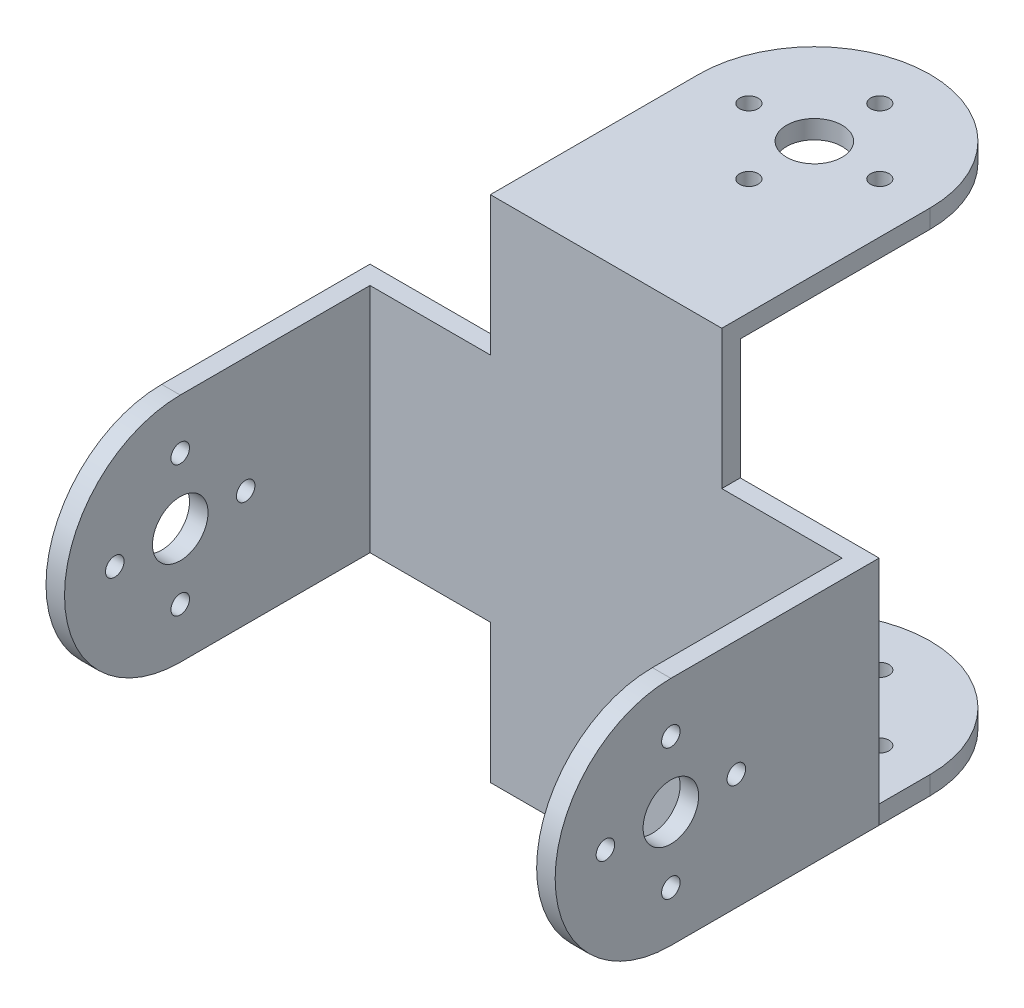
SolidWorks part; units mm, degrees
ref_plane "前视基准面" through (0, 0, 0) normal (0, 0, 1) x (1, 0, 0)
ref_plane "上视基准面" through (0, 0, 0) normal (0, 1, 0) x (1, 0, 0)
ref_plane "右视基准面" through (0, 0, 0) normal (1, 0, 0) x (0, 0, -1)
sketch "草图1" plane through (0, 0, 0) normal (0, 0, 1) x (1, 0, 0)
  line L0 (0, 0) -> (50000, 0) construction
  line L1 (0, 0) -> (0, 50000) construction
  line L2 (-27.5, 12.5) -> (27.5, 12.5)
  line L3 (-27.5, 27.5) -> (27.5, 27.5)
  line L4 (-27.5, 27.5) -> (-27.5, -27.5)
  line L5 (-27.5, -27.5) -> (27.5, -27.5)
  line L6 (27.5, 27.5) -> (27.5, -27.5)
  line L7 (-27.5, -12.5) -> (27.5, -12.5)
  line L8 (-12.5, -12.5) -> (-12.5, -27.5)
  line L9 (12.5, -12.5) -> (12.5, -27.5)
  line L10 (12.5, 12.5) -> (12.5, 27.5)
  line L11 (-12.5, 12.5) -> (-12.5, 27.5)
  dimension "D1" = 55
  dimension "D2" = 55
  dimension "D3" = 12.5
  dimension "D4" = 25
extrude "凸台-拉伸2" add sketch "草图1" along normal blind 2 contours L4 L7 L6 L2 | L11 L2 L10 L3 | L9 L7 L8 L5
sketch "草图3" plane through (0, 0, 2) normal (0, 0, 1) x (1, 0, 0)
  line L0 (0, 0) -> (50000, 0) construction
  line L1 (0, 0) -> (0, 50000) construction
  line L2 (-25.5, 12.5) -> (-25.5, -12.5)
  line L3 (-27.5, 12.5) -> (-12.5, 12.5) construction
  line L4 (-27.5, -12.5) -> (-12.5, -12.5) construction
  line L5 (-27.5, 12.5) -> (-27.5, -12.5) construction
  line L6 (25.5, 12.5) -> (25.5, -12.5)
  line L7 (25.5, 12.5) -> (27.5, 12.5)
  line L8 (27.5, 12.5) -> (27.5, -12.5)
  line L9 (27.5, -12.5) -> (25.5, -12.5)
  line L10 (-25.5, -12.5) -> (-27.5, -12.5)
  line L11 (-27.5, -12.5) -> (-27.5, 12.5)
  line L12 (-27.5, 12.5) -> (-25.5, 12.5)
  line M15 (12.5, -12.5) -> (27.5, -12.5)
  line M16 (27.5, -12.5) -> (27.5, 12.5)
  line M17 (27.5, 12.5) -> (12.5, 12.5)
  dimension "D1" = 2
extrude "凸台-拉伸3" add sketch "草图3" along normal blind 33 contours L6 M17 M15 M16 | L12 L2 L10 L11
sketch "草图4" plane through (0, 0, 0) normal (0, 0, -1) x (-1, 0, 0)
  line L0 (-12.5, 25.5) -> (12.5, 25.5)
  line L1 (-12.5, 12.5) -> (-12.5, 27.5) construction
  line L2 (12.5, 12.5) -> (12.5, 27.5) construction
  line L3 (-12.5, -25.5) -> (12.5, -25.5)
  line L4 (-12.5, -12.5) -> (-12.5, -27.5) construction
  line L5 (12.5, -12.5) -> (12.5, -27.5) construction
  line L6 (12.5, 27.5) -> (-12.5, 27.5) construction
  line L7 (12.5, -27.5) -> (-12.5, -27.5) construction
  line L8 (12.5, 25.5) -> (12.5, 27.5)
  line L9 (12.5, 27.5) -> (-12.5, 27.5)
  line L10 (-12.5, 27.5) -> (-12.5, 25.5)
  line L11 (-12.5, -25.5) -> (-12.5, -27.5)
  line L12 (-12.5, -27.5) -> (12.5, -27.5)
  line L13 (12.5, -27.5) -> (12.5, -25.5)
  dimension "D1" = 2
  dimension "D2" = 2
extrude "凸台-拉伸4" add sketch "草图4" along normal blind 33
sketch "草图5" plane through (-27.5, 0, 0) normal (-1, 0, 0) x (0, 0, 1)
  line L0 (0, 0) -> (50000, 0) construction
  line L1 (35, -12.5) -> (35, 12.5) construction
  line L2 (22.5, 12.5) -> (35, 12.5)
  line L3 (35, 12.5) -> (35, -12.5)
  line L4 (35, -12.5) -> (22.5, -12.5)
  line L5 (22.5, 0) -> (22.5, 50000) construction
  circle A0 centre (22.5, 0) radius 12.5
  circle A1 centre (29.6825, 0) radius 1
  circle A2 centre (15.3175, 0) radius 1
  circle A3 centre (22.5, 6.9578) radius 1
  circle A4 centre (22.5, -6.9578) radius 1
  line M3 (0, -12.5) -> (35, -12.5)
  line M4 (35, -12.5) -> (35, 12.5)
  line M5 (35, 12.5) -> (0, 12.5)
  dimension "D1" = 12.5
  dimension "D2" = 10
extrude "切除-拉伸2" cut sketch "草图5" against normal through all contours A0 L3 M5 | A0 M3 M4 | A1 | A3 | A2 | A4
sketch "草图6" plane through (0, 27.5, 0) normal (0, 1, 0) x (1, 0, 0)
  line L0 (0, 0) -> (0, 50000) construction
  line L1 (-12.5, 33) -> (12.5, 33) construction
  line L2 (-12.5, 20.5) -> (-12.5, 33)
  line L3 (-12.5, 33) -> (12.5, 33)
  line L4 (12.5, 33) -> (12.5, 20.5)
  line L5 (0.3699, 20.5) -> (50000.3699, 20.5) construction
  circle A0 centre (0, 20.5) radius 12.5
  circle A1 centre (0, 28.1221) radius 1
  circle A2 centre (0, 12.8779) radius 1
  circle A3 centre (-6.4732, 20.5) radius 1
  circle A4 centre (6.4732, 20.5) radius 1
  line M6 (12.5, -2) -> (12.5, 33)
  line M7 (12.5, 33) -> (-12.5, 33)
  line M8 (-12.5, 33) -> (-12.5, -2)
  dimension "D1" = 12.5
  dimension "D2" = 10
extrude "切除-拉伸3" cut sketch "草图6" against normal through all contours A0 L3 M8 | A0 M6 M7 | A4 | A1 | A3 | A2
sketch "草图7" plane through (0, 27.5, 0) normal (0, 1, 0) x (1, 0, 0)
  line L0 (-6.4732, 20.5) -> (49993.5268, 20.5) construction
  line L1 (0, 12.8779) -> (0, 50012.8779) construction
  circle A0 centre (0, 20.5) radius 3
extrude "切除-拉伸4" cut sketch "草图7" against normal through all contours A0
sketch "草图8" plane through (27.5, 0, 0) normal (1, 0, 0) x (0, 0, -1)
  line L0 (-15.3175, 0) -> (49984.6825, 0) construction
  line L1 (-22.5, -6.9578) -> (-22.5, 49993.0422) construction
  circle A0 centre (-22.5, 0) radius 3
extrude "切除-拉伸5" cut sketch "草图8" against normal through all
sketch "草图9" plane through (27.5, 0, 0) normal (1, 0, 0) x (0, 0, -1)
  circle A0 centre (-22.5, 0) radius 3
  circle A1 centre (-22.5, 0) radius 12.5
extrude "凸台-拉伸5" add sketch "草图9" against normal blind 2
sketch "草图10" plane through (-27.5, 0, 0) normal (-1, 0, 0) x (0, 0, 1)
  circle A0 centre (22.5, 0) radius 12.5
  circle A1 centre (22.5, 0) radius 3
extrude "凸台-拉伸6" add sketch "草图10" against normal blind 2
sketch "草图11" plane through (-27.5, 0, 0) normal (-1, 0, 0) x (0, 0, 1)
  line L0 (22.5, 0) -> (22.5, 50000) construction
  line L1 (22.5, 0) -> (50022.5, 0) construction
  line L2 (22.5, 7.0711) -> (22.5, 0)
  line L3 (22.5, 0) -> (29.5711, 0)
  line L4 (22.5, 0) -> (-35332.8391, 35355.3391) construction
  circle A1 centre (22.5, 7.0711) radius 1
  circle A2 centre (29.5711, 0) radius 1
  circle A3 centre (22.5, -7.0711) radius 1
  circle A4 centre (15.4289, 0) radius 1
  dimension "D1" = 10
extrude "切除-拉伸6" cut sketch "草图11" against normal through all contours A4 | A1 | A2 | A3
sketch "草图12" plane through (0, 27.5, 0) normal (0, 1, 0) x (1, 0, 0)
  circle A0 centre (0, 20.5) radius 12.5
  circle A1 centre (0, 20.5) radius 3
extrude "凸台-拉伸7" add sketch "草图12" against normal blind 2
sketch "草图13" plane through (0, -27.5, 0) normal (0, -1, 0) x (1, 0, 0)
  circle A0 centre (0, -20.5) radius 3
  circle A1 centre (0, -20.5) radius 12.5
extrude "凸台-拉伸8" add sketch "草图13" against normal blind 2
sketch "草图14" plane through (0, -27.5, 0) normal (0, -1, 0) x (-1, 0, 0)
  line L0 (0, 20.5) -> (-50000, 20.5) construction
  line L1 (0, 20.5) -> (0, -49979.5) construction
  line L2 (0, 13.4289) -> (0, 20.5)
  line L3 (0, 20.5) -> (-7.0711, 20.5)
  line L4 (0, 20.5) -> (35355.3391, -35334.8391) construction
  circle A2 centre (0, 13.4289) radius 1
  circle A3 centre (-7.0711, 20.5) radius 1
  circle A4 centre (0, 27.5711) radius 1
  circle A5 centre (7.0711, 20.5) radius 1
  dimension "D1" = 10
extrude "切除-拉伸7" cut sketch "草图14" against normal through all
